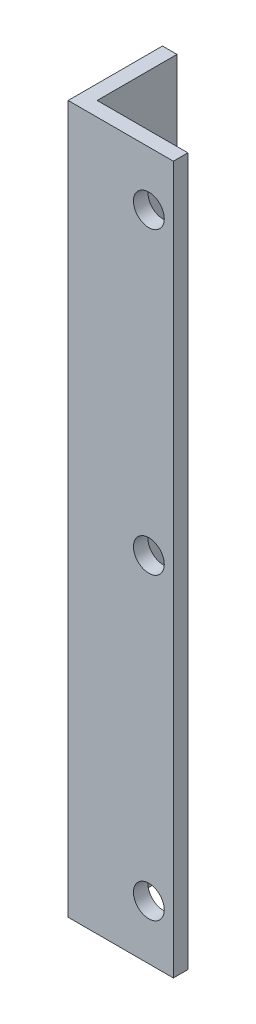
SolidWorks part; units mm, degrees
ref_plane "Alzado" through (0, 0, 0) normal (0, 0, 1) x (1, 0, 0)
ref_plane "Planta" through (0, 0, 0) normal (0, 1, 0) x (1, 0, 0)
ref_plane "Vista lateral" through (0, 0, 0) normal (1, 0, 0) x (0, 0, -1)
sketch "Croquis1" plane through (0, 0, 0) normal (0, 1, 0) x (1, 0, 0)
  line L0 (0, 0) -> (25, 0)
  line L1 (25, 0) -> (25, -3)
  line L2 (25, -3) -> (0, -3)
  line L3 (0, -3) -> (0, 0)
extrude "Saliente-Extruir1" add sketch "Croquis1" along normal blind 195
sketch "Croquis2" plane through (0, 0, 3) normal (0, 0, 1) x (1, 0, 0)
  line L0 (0, 195) -> (0, 0) construction
  line L1 (0, 0) -> (25, 0) construction
  line L2 (0, 195) -> (25, 195) construction
  circle A0 centre (18.25, 180) radius 4.25
  circle A1 centre (18.25, 97.5) radius 4.25
  circle A2 centre (18.25, 15) radius 4.25
  dimension "D1" = 18.25
  dimension "D2" = 15
  dimension "D3" = 97.5
  dimension "D4" = 15
extrude "Cortar-Extruir1" cut sketch "Croquis2" against normal blind 195
sketch "Croquis3" plane through (0, 195, 0) normal (0, 1, 0) x (1, 0, 0)
  line L1 (0, -3) -> (-4, -3)
  line L2 (0, -3) -> (0, 22)
  line L3 (0, 22) -> (-4, 22)
  line L4 (-4, -3) -> (-4, 22)
  dimension "D1" = 4
extrude "Saliente-Extruir2" add sketch "Croquis3" against normal blind 195
sketch "Croquis4" plane through (0, 0, 3) normal (0, 0, 1) x (1, 0, 0)
  line L1 (25, 195) -> (-4, 195)
  line L2 (25, 195) -> (25, 0)
  line L3 (25, 0) -> (-4, 0)
  line L4 (-4, 195) -> (-4, 0)
  circle A0 centre (18.25, 15) radius 4.25
  circle A1 centre (18.25, 97.5) radius 4.25
  circle A2 centre (18.25, 180) radius 4.25
extrude "Saliente-Extruir3" add sketch "Croquis4" along normal blind 1
